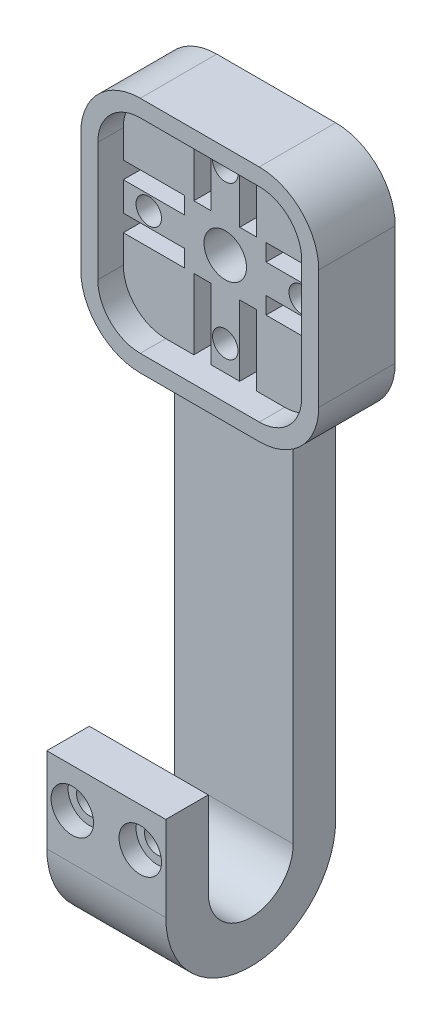
SolidWorks part; units mm, degrees
material "6063-O"
ref_plane "Ön Düzlem" through (0, 0, 0) normal (0, 0, 1) x (1, 0, 0)
ref_plane "Üst Düzlem" through (0, 0, 0) normal (0, 1, 0) x (1, 0, 0)
ref_plane "Sağ Düzlem" through (0, 0, 0) normal (1, 0, 0) x (0, 0, -1)
sketch "Çizim1" plane through (0, 0, 0) normal (0, 0, 1) x (1, 0, 0)
  line L0 (17, 7) -> (17, -7)
  line L1 (-7, 12) -> (7, 12)
  line L2 (-12, 7) -> (-12, -7)
  line L3 (-7, -12) -> (7, -12)
  line L4 (12, 7) -> (12, -7)
  line L5 (-12, 12) -> (12, -12) construction
  line L6 (-12, -12) -> (12, 12) construction
  line L7 (-7, -17) -> (7, -17)
  line L8 (-17, 7) -> (-17, -7)
  line L9 (-7, 17) -> (7, 17)
  arc A0 (-12, -7) -> (-7, -12) centre (-7, -7) ccw
  arc A1 (7, -12) -> (12, -7) centre (7, -7) ccw
  arc A2 (7, 12) -> (12, 7) centre (7, 7) cw
  arc A3 (-7, 12) -> (-12, 7) centre (-7, 7) ccw
  arc A4 (7, 17) -> (17, 7) centre (7, 7) cw
  arc A5 (7, -17) -> (17, -7) centre (7, -7) ccw
  arc A6 (-17, -7) -> (-7, -17) centre (-7, -7) ccw
  arc A7 (-7, 17) -> (-17, 7) centre (-7, 7) ccw
  point P0 (0, 0)
  dimension "D3" = 5
  dimension "D1" = 24
  dimension "D2" = 24
  dimension "D4" = 5
extrude "Yükseklik-Ekstrüzyon1" add sketch "Çizim1" along normal blind 9
sketch "Çizim2" plane through (0, 0, 0) normal (0, 0, 1) x (1, 0, 0)
  line L0 (-7, -12) -> (7, -12) construction
  line L1 (12, -7) -> (12, 7) construction
  line L2 (7, 12) -> (-7, 12) construction
  line L3 (-12, 7) -> (-12, -7) construction
  line L4 (-7, -12) -> (7, -12)
  line L5 (12, -7) -> (12, 7)
  line L6 (7, 12) -> (-7, 12)
  line L7 (-12, 7) -> (-12, -7)
  arc A0 (-12, -7) -> (-7, -12) centre (-7, -7) ccw construction
  arc A1 (7, -12) -> (12, -7) centre (7, -7) ccw construction
  arc A2 (12, 7) -> (7, 12) centre (7, 7) ccw construction
  arc A3 (-7, 12) -> (-12, 7) centre (-7, 7) ccw construction
  arc A4 (-12, -7) -> (-7, -12) centre (-7, -7) ccw
  arc A5 (7, -12) -> (12, -7) centre (7, -7) ccw
  arc A6 (12, 7) -> (7, 12) centre (7, 7) ccw
  arc A7 (-7, 12) -> (-12, 7) centre (-7, 7) ccw
extrude "Yükseklik-Ekstrüzyon2" add sketch "Çizim2" along normal blind 6
sketch "Çizim3" plane through (0, 0, 6) normal (0, 0, 1) x (1, 0, 0)
  line L0 (-3.7, 12) -> (-1.7, 12)
  line L1 (-1.7, 12) -> (-1.7, 3.7)
  line L2 (1.7, 12) -> (1.7, 3.7)
  line L3 (-3.7, 12) -> (-3.7, 3.7)
  line L4 (7, 12) -> (-7, 12) construction
  line L5 (-12, 3.7) -> (-12, 1.7)
  line L6 (-12, -1.7) -> (-12, -3.7)
  line L7 (-12, -1.7) -> (-4.8, -1.7)
  line L12 (3.7, 12) -> (3.7, 3.7)
  line L13 (-3.7, 3.7) -> (-1.7, 3.7)
  line L14 (-3.7, 12) -> (-1.7, 12)
  line L15 (1.7, 12) -> (3.7, 12)
  line L16 (3.7, 3.7) -> (1.7, 3.7)
  line L25 (3.7, -12) -> (1.7, -12)
  line L26 (1.7, -12) -> (1.7, -3.7)
  line L27 (3.7, -3.7) -> (1.7, -3.7)
  line L28 (3.7, -12) -> (3.7, -3.7)
  line L29 (-3.7, -3.7) -> (-1.7, -3.7)
  line L30 (-1.7, -12) -> (-1.7, -3.7)
  line L31 (-1.7, -12) -> (-3.7, -12)
  line L32 (-3.7, -12) -> (-3.7, -3.7)
  line L41 (-3.7, 3.7) -> (-3.7, 1.7) [skipped]
  line L42 (-12, 1.7) -> (-12, 3.7) [skipped]
  line L43 (-12, 3.7) -> (-3.7, 3.7) [skipped]
  line L44 (-12, 1.7) -> (-3.7, 1.7) [skipped]
  line L45 (-12, -1.7) -> (-3.7, -1.7) [skipped]
  line L46 (-12, -3.7) -> (-3.7, -3.7) [skipped]
  line L47 (-12, -3.7) -> (-12, -1.7) [skipped]
  line L48 (-3.7, -3.7) -> (-3.7, -1.7) [skipped]
  line L49 (3.7, -3.7) -> (3.7, -1.7) [skipped]
  line L50 (12, -1.7) -> (12, -3.7) [skipped]
  line L51 (12, -1.7) -> (3.7, -1.7) [skipped]
  line L52 (12, -3.7) -> (3.7, -3.7) [skipped]
  line L53 (12, 1.7) -> (3.7, 1.7) [skipped]
  line L54 (12, 3.7) -> (3.7, 3.7) [skipped]
  line L55 (3.7, 3.7) -> (3.7, 1.7) [skipped]
  line L56 (12, 3.7) -> (12, 1.7) [skipped]
  line L57 (-12, 1.7) -> (-4.8, 1.7)
  line L58 (-12, -3.7) -> (-4.8, -3.7)
  line L59 (-12, 3.7) -> (-4.8, 3.7)
  line L60 (-4.8, 3.7) -> (-4.8, 1.7)
  line L61 (-4.8, -1.7) -> (-4.8, -3.7)
  line L62 (4.8, 3.7) -> (4.8, 1.7)
  line L63 (12, 1.7) -> (12, 3.7)
  line L64 (12, 1.7) -> (4.8, 1.7)
  line L65 (7, 12) -> (-7, 12) construction
  line L66 (12, 3.7) -> (4.8, 3.7)
  line L67 (12, -1.7) -> (4.8, -1.7)
  line L68 (4.8, -3.7) -> (4.8, -1.7)
  line L69 (12, -3.7) -> (12, -1.7)
  line L70 (12, -3.7) -> (4.8, -3.7)
  line L71 (-12, 7) -> (-12, -7) construction
  line L73 (12, -7) -> (12, 7) construction
  point P14 (0, 12)
  point P40 (-12, 0)
  point P43 (12, 0)
  point P47 (0, 0)
  line M27 (-7, -12) -> (7, -12)
  line M29 (12, -7) -> (12, 7)
  line M31 (7, 12) -> (-7, 12)
  line M33 (-12, 7) -> (-12, -7)
  dimension "D2" = 4
  dimension "D1" = 8.3
  dimension "D3" = 2
  dimension "D8" = 7.2
  dimension "D9" = 1.7
  dimension "D10" = 1.7
  dimension "D11" = 1.7
  dimension "D12" = 1.7
  dimension "D13" = 1.7
  dimension "D14" = 1.7
  dimension "D4" = 2
  dimension "D5" = 2
  dimension "D6" = 2
  dimension "D7" = 2
sketch "Çizim4" plane through (0, 0, 6) normal (0, 0, 1) x (1, 0, 0)
  line L0 (7, 12) -> (-7, 12) construction
  circle A0 centre (0, 9) radius 1.5
  circle A1 centre (0, 0) radius 2.5
  circle A2 centre (9, 0) radius 1.5
  circle A3 centre (0, -9) radius 1.5
  circle A4 centre (-9, 0) radius 1.5
  point P14 (0, 0)
  dimension "D1" = 3
  dimension "D2" = 5
  dimension "D4" = 3
  dimension "D3" = 4
extrude "Kes-Ekstrüzyon2" cut sketch "Çizim4" against normal blind 6.5
sketch "Çizim5" plane through (0, 0, 0) normal (0, 0, 1) x (1, 0, 0)
  line L0 (-7, -17) -> (7, -17)
  line L1 (7, -17) -> (7, -32)
  line L2 (7, -32) -> (-7, -32)
  line L3 (-7, -32) -> (-7, -17)
  dimension "D1" = 15
extrude "Yükseklik-Ekstrüzyon3" add sketch "Çizim5" along normal blind 5
sketch "Çizim6" plane through (0, 0, 0) normal (1, 0, 0) x (0, 0, -1)
  line L5 (0, -32) -> (-5, -32)
  line L6 (0, -32) -> (0, -57)
  line L7 (-5, -32) -> (-5, -57)
  line L10 (-15, -57) -> (-15, -47)
  line L11 (-20, -47) -> (-15, -47)
  line L12 (-20, -57) -> (-20, -47)
  arc A2 (-5, -57) -> (-15, -57) centre (-10, -57) cw
  arc A3 (0, -57) -> (-20, -57) centre (-10, -57) cw
  dimension "D1" = 25
extrude "Yükseklik-Ekstrüzyon4" add sketch "Çizim6" along normal mid plane 14
extrude "Kes-Ekstrüzyon3" cut sketch "Çizim3" against normal blind 3 contours L66 L62 L64 M29 | L16 L12 L2 M31 | L3 L13 L1 M31 | L60 L59 L57 M33 | L61 L7 L58 M33 | L32 L30 L29 M27 | L28 L27 L26 M27 | L70 L67 L68 M29
ref_plane "Düzlem1" through (0, 0, 20) normal (0, 0, 1) x (1, 0, 0)
sketch "Çizim8" plane through (0, 0, 20) normal (0, 0, 1) x (1, 0, 0)
  line L0 (7, -47) -> (-7, -47) construction
  line L1 (0, -47) -> (0, -48.419)
  circle A0 centre (-4, -51.6166) radius 1.5
  circle A1 centre (4, -51.6166) radius 1.5
  point P4 (0, -47)
  dimension "D2" = 3
  dimension "D1" = 4
extrude "Kes-Ekstrüzyon5" cut sketch "Çizim8" against normal blind 10 contours A0 | A1
sketch "Çizim9" plane through (0, 0, 0) normal (0, 0, -1) x (-1, 0, 0)
  circle A24 centre (0, 9) radius 2.5
  circle A25 centre (0, 0) radius 4
  circle A26 centre (9, 0) radius 2.5
  circle A27 centre (0, -9) radius 2.5
  circle A28 centre (-9, 0) radius 2.5
  point P11 (0, 0)
  dimension "D1" = 5
  dimension "D2" = 8
  dimension "D3" = 4
extrude "Kes-Ekstrüzyon6" cut sketch "Çizim9" against normal blind 2
sketch "Çizim10" plane through (0, 0, 20) normal (0, 0, 1) x (1, 0, 0)
  circle A0 centre (-4, -51.6166) radius 2.5
  circle A1 centre (4, -51.6166) radius 2.5
  dimension "D1" = 5
extrude "Kes-Ekstrüzyon7" cut sketch "Çizim10" against normal blind 2
sketch "Çizim11" plane through (0, 0, 9) normal (0, 0, 1) x (1, 0, 0)
  line L0 (7, 14) -> (-7, 14)
  line L1 (-14, 7) -> (-14, -7)
  line L2 (-7, -14) -> (7, -14)
  line L3 (14, -7) -> (14, 7)
  line L4 (7, 17) -> (-7, 17)
  line L5 (-17, 7) -> (-17, -7)
  line L6 (-7, -17) -> (7, -17)
  line L7 (17, -7) -> (17, 7)
  line L8 (7, 17) -> (-7, 17)
  line L9 (-17, 7) -> (-17, -7)
  line L10 (-7, -17) -> (7, -17)
  line L11 (17, -7) -> (17, 7)
  arc A0 (14, 7) -> (7, 14) centre (7, 7) ccw
  arc A1 (-7, 14) -> (-14, 7) centre (-7, 7) ccw
  arc A2 (-14, -7) -> (-7, -14) centre (-7, -7) ccw
  arc A3 (7, -14) -> (14, -7) centre (7, -7) ccw
  arc A4 (17, 7) -> (7, 17) centre (7, 7) ccw
  arc A5 (-7, 17) -> (-17, 7) centre (-7, 7) ccw
  arc A6 (-17, -7) -> (-7, -17) centre (-7, -7) ccw
  arc A7 (7, -17) -> (17, -7) centre (7, -7) ccw
  arc A8 (17, 7) -> (7, 17) centre (7, 7) ccw
  arc A9 (-7, 17) -> (-17, 7) centre (-7, 7) ccw
  arc A10 (-17, -7) -> (-7, -17) centre (-7, -7) ccw
  arc A11 (7, -17) -> (17, -7) centre (7, -7) ccw
  dimension "D1" = 0
  dimension "D2" = 3
extrude "Kes-Ekstrüzyon8" cut sketch "Çizim11" against normal blind 10
sketch "Çizim12" plane through (0, 0, 0) normal (0, 0, 1) x (1, 0, 0)
  line L0 (-7, -14) -> (-7, -17)
  line L1 (-7, -17) -> (7, -17)
  line L2 (7, -17) -> (7, -14)
  line L3 (7, -14) -> (-7, -14)
extrude "Yükseklik-Ekstrüzyon5" add sketch "Çizim12" along normal blind 5
